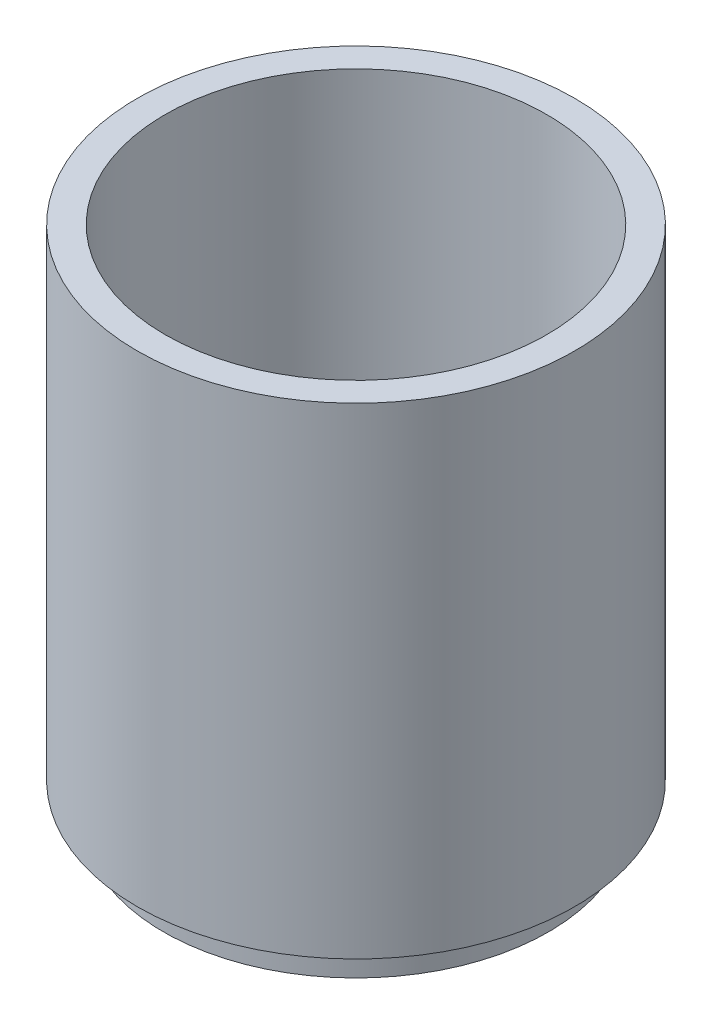
SolidWorks part; units mm, degrees
ref_plane "Front Plane" through (0, 0, 0) normal (0, 0, 1) x (1, 0, 0)
ref_plane "Top Plane" through (0, 0, 0) normal (0, 1, 0) x (1, 0, 0)
ref_plane "Right Plane" through (0, 0, 0) normal (1, 0, 0) x (0, 0, -1)
sketch "Sketch1" plane through (0, 0, 0) normal (0, 1, 0) x (1, 0, 0)
  circle A0 centre (0, 0) radius 31.75
  dimension "D1" = 63.5
extrude "Boss-Extrude1" add sketch "Sketch1" along normal blind 69.85
sketch "Sketch2" plane through (0, 69.85, 0) normal (0, 1, 0) x (1, 0, 0)
  circle A0 centre (0, 0) radius 27.686
  dimension "D1" = 55.372
extrude "Cut-Extrude1" cut sketch "Sketch2" against normal blind 63.5
sketch "Sketch3" plane through (0, 0, 0) normal (0, -1, 0) x (1, 0, 0)
  circle A0 centre (0, 0) radius 27.94
  dimension "D1" = 55.88
extrude "Boss-Extrude2" add sketch "Sketch3" along normal blind 5.08
